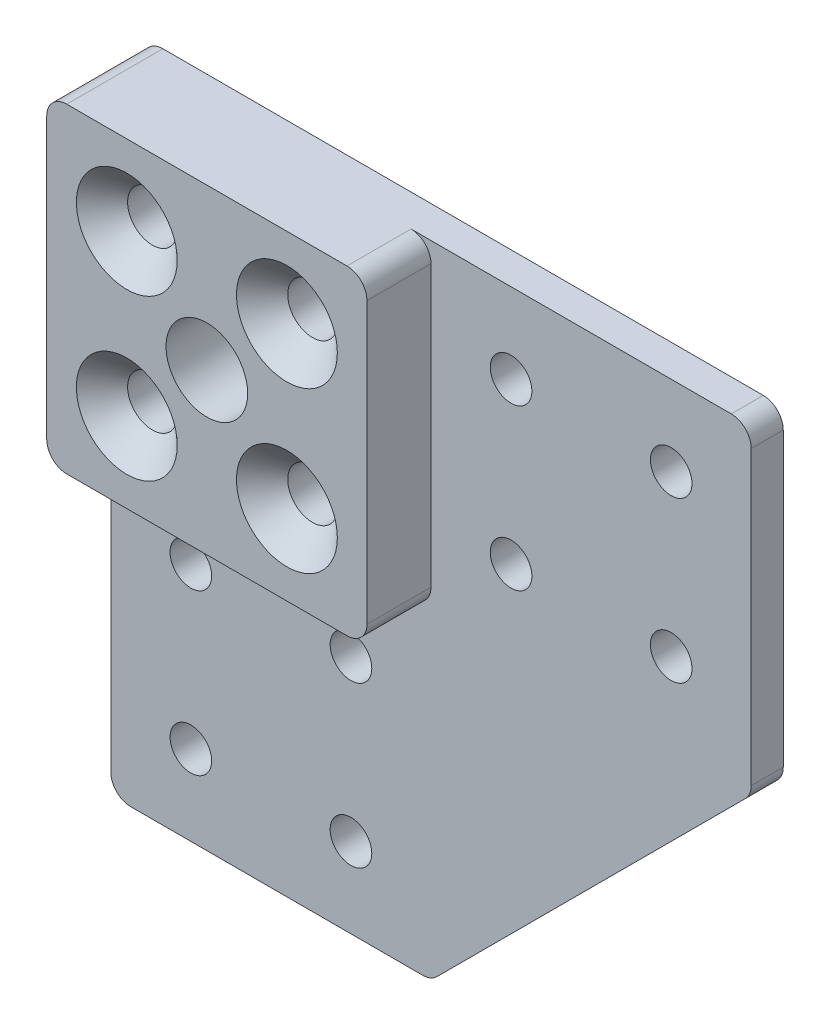
SolidWorks part; units mm, degrees
ref_plane "Спереди" through (0, 0, 0) normal (0, 0, 1) x (1, 0, 0)
ref_plane "Сверху" through (0, 0, 0) normal (0, 1, 0) x (1, 0, 0)
ref_plane "Справа" through (0, 0, 0) normal (1, 0, 0) x (0, 0, -1)
sketch "Эскиз1" plane through (0, 0, 0) normal (0, 0, 1) x (1, 0, 0)
  line L5 (0, 0) -> (80, 0)
  line L6 (80, 0) -> (80, -40)
  line L7 (80, -40) -> (40, -80)
  line L8 (40, -80) -> (0, -80)
  line L9 (0, -80) -> (0, 0)
  dimension "D3" = 40
  dimension "D4" = 40
  dimension "D1" = 80
  dimension "D2" = 80
extrude "Бобышка-Вытянуть1" add sketch "Эскиз1" along normal blind 4
sketch "Эскиз2" plane through (0, 0, 4) normal (0, 0, 1) x (1, 0, 0)
  line L1 (0, 0) -> (40, 0)
  line L2 (0, 0) -> (0, -40)
  line L3 (0, -40) -> (40, -40)
  line L4 (40, 0) -> (40, -40)
  dimension "D1" = 40
  dimension "D2" = 40
extrude "Бобышка-Вытянуть2" add sketch "Эскиз2" along normal blind 8
sketch "Эскиз3" plane through (0, 0, 0) normal (0, 0, -1) x (-1, 0, 0)
  line L0 (-25.6, -27.3005) -> (-25.6, -31.9302)
  line L4 (-14.4, -31.9302) -> (-14.4, -27.3005)
  line L5 (-13, -25.6) -> (-8.0698, -25.6)
  line L9 (-8.0698, -14.4) -> (-13, -14.4)
  line L10 (-14.4, -12.6995) -> (-14.4, -8.0698)
  line L14 (-25.6, -8.0698) -> (-25.6, -12.6995)
  line L15 (-27, -14.4) -> (-31.9302, -14.4)
  line L19 (-31.9302, -25.6) -> (-27, -25.6)
  line L20 (0, 0) -> (0, -80) construction
  line L21 (-10.185, -20) -> (-13.4639, -14.3209)
  line L22 (-15.0925, -11.5) -> (-24.9075, -11.5)
  line L23 (-24.9075, -11.5) -> (-25.6, -12.6995)
  line L24 (-29.815, -20) -> (-26.5361, -25.6791)
  line L25 (-24.9075, -28.5) -> (-15.0925, -28.5)
  line L26 (-15.0925, -28.5) -> (-14.4, -27.3005)
  line L27 (-80, 0) -> (0, 0) construction
  line L28 (-25.6, -31.9302) -> (-14.4, -31.9302)
  line L29 (-8.0698, -25.6) -> (-8.0698, -14.4)
  line L30 (-31.9302, -25.6) -> (-31.9302, -14.4)
  line L31 (-25.6, -8.0698) -> (-14.4, -8.0698)
  line L32 (-26.5361, -14.3209) -> (-29.815, -20)
  line L33 (-14.4, -12.6995) -> (-15.0925, -11.5)
  line L34 (-25.6, -27.3005) -> (-24.9075, -28.5)
  line L35 (-13.4639, -25.6791) -> (-10.185, -20)
  arc A4 (-13, -25.6) -> (-13.4639, -25.6791) centre (-13, -27) ccw
  arc A14 (-27, -14.4) -> (-26.5361, -14.3209) centre (-27, -13) ccw
  circle A20 centre (-20, -20) radius 8.5 construction
  arc A21 (-26.5361, -25.6791) -> (-27, -25.6) centre (-27, -27) ccw
  arc A22 (-13.4639, -14.3209) -> (-13, -14.4) centre (-13, -13) ccw
  dimension "D4" = 17
  dimension "D2" = 20
  dimension "D3" = 20
extrude "Бобышка-Вытянуть3" [suppressed] add sketch "Эскиз3" along normal blind 8 draft 0.1
hole_wizard "Зенковка для винта с полупотайной головкой M61" positions "Трехмерный эскиз1" profile "Эскиз4" countersink size "M6" standard "ISO" end condition through all
sketch3d "Трехмерный эскиз1"
  point P0 (10, -30, 12)
  point P2 (10, -10, 12)
  point P4 (30, -10, 12)
  point P6 (30, -30, 12)
  point P8 (0, 0, 0)
  point P9 (0, 0, 0)
  point P10 (0, 0, 0)
  point P11 (0, 0, 0)
  point P12 (0, 0, 0)
  dimension "D1" = 20
  dimension "D2" = 20
  dimension "D3" = 10
  dimension "D4" = 10
sketch "Эскиз4" plane through (10, -30, 12) normal (1, 0, 0) x (0, -1, 0)
  line L0 (0, 0) -> (0, 12)
  line L1 (0, 12) -> (3.1, 12)
  line L2 (3.1, 12) -> (3.1, 3.2)
  line L3 (3.1, 3.2) -> (6.3, 0)
  line L5 (6.3, 0) -> (0, 0)
  line L6 (-3.1, 3.2) -> (-6.3, 0) construction
  line L11 (0, -6.35) -> (0, 107.95) construction
  dimension "Диаметр сквозного отверстия" = 6.2
  dimension "Глубина сквозного отверстия" = 12
  dimension "Диаметр передней зенковки" = 12.6
  dimension "Угол передней зенковки" = 90
sketch "Эскиз5" plane through (0, 0, 12) normal (0, 0, 1) x (1, 0, 0)
  line L0 (0, 0) -> (0, -40) construction
  line L1 (40, 0) -> (0, 0) construction
  circle A0 centre (20, -20) radius 5.1
  dimension "D1" = 10.2
  dimension "D3" = 20
  dimension "D2" = 20
extrude "Вырез-Вытянуть1" cut sketch "Эскиз5" against normal through all
sketch "Эскиз6" plane through (0, 0, 4) normal (0, 0, 1) x (1, 0, 0)
  line L0 (0, -40) -> (0, -80) construction
  line L1 (0, -40) -> (40, -40) construction
  line L2 (10, -50) -> (30, -50) construction
  line L3 (10, -50) -> (10, -70) construction
  line L4 (40, -40) -> (35395.3391, -35395.3391) construction
  line L5 (40, -80) -> (80, -40) construction
  circle A0 centre (10, -50) radius 2.6
  circle A1 centre (30, -50) radius 2.6
  circle A2 centre (30, -70) radius 2.6
  circle A3 centre (10, -70) radius 2.6
  circle A4 centre (70, -10) radius 2.6
  circle A5 centre (70, -30) radius 2.6
  circle A6 centre (50, -30) radius 2.6
  circle A7 centre (50, -10) radius 2.6
  dimension "D1" = 5.2
  dimension "D2" = 10
  dimension "D3" = 10
  dimension "D6" = 90
  dimension "D7" = 20
  dimension "D8" = 20
  dimension "D4" = 2
  dimension "D5" = 2
extrude "Вырез-Вытянуть2" cut sketch "Эскиз6" against normal through all
fillet "Скругление1" radius 2.5 8 edges at (80, 0, 2) (80, -40, 2) (40, -80, 2) (0, -80, 2) (0, 0, 6) (40, 0, 8) (40, -40, 8) (0, -40, 8)
